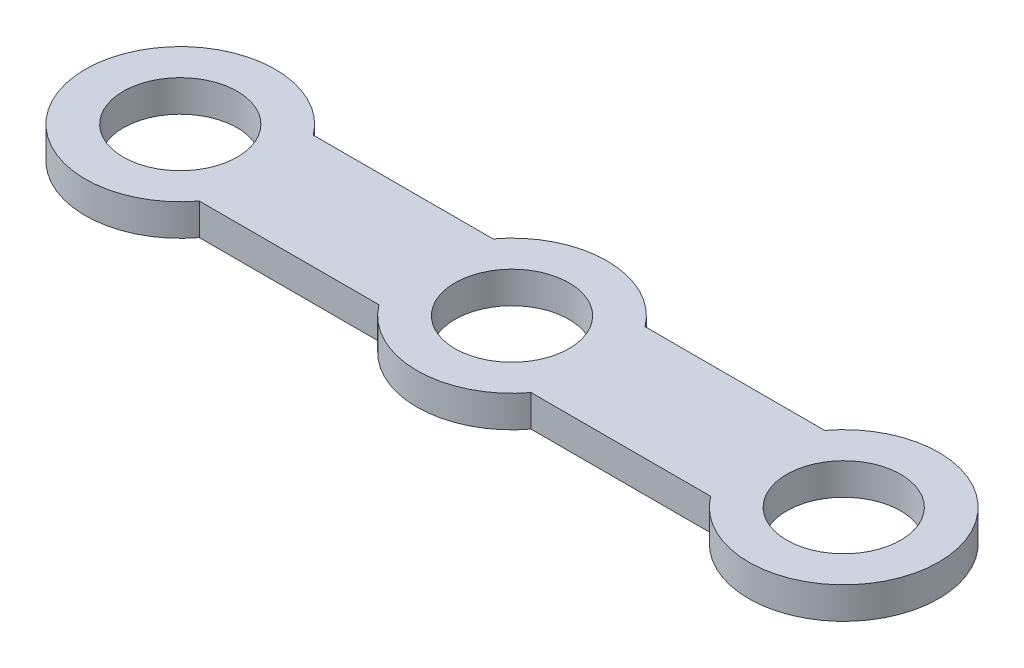
SolidWorks part; units mm, degrees
ref_plane "Front Plane" through (0, 0, 0) normal (0, 0, 1) x (1, 0, 0)
ref_plane "Top Plane" through (0, 0, 0) normal (0, 1, 0) x (1, 0, 0)
ref_plane "Right Plane" through (0, 0, 0) normal (1, 0, 0) x (0, 0, -1)
sketch "Sketch1" plane through (0, 0, 0) normal (0, 1, 0) x (1, 0, 0)
  line L0 (0, 0) -> (1047.091, 0) construction
  line L1 (120, 90) -> (927.091, 90)
  line L2 (120, -90) -> (927.091, -90)
  circle A0 centre (0, 0) radius 90
  circle A1 centre (523.5455, 0) radius 90
  circle A2 centre (1047.091, 0) radius 90
  circle A3 centre (0, 0) radius 150
  circle A4 centre (523.5455, 0) radius 150
  circle A5 centre (1047.091, 0) radius 150
  dimension "D2" = 300
  dimension "D3" = 180
  dimension "D4" = 180
  dimension "D1" = 1047.091
extrude "Boss-Extrude1" add sketch "Sketch1" along normal blind 50
